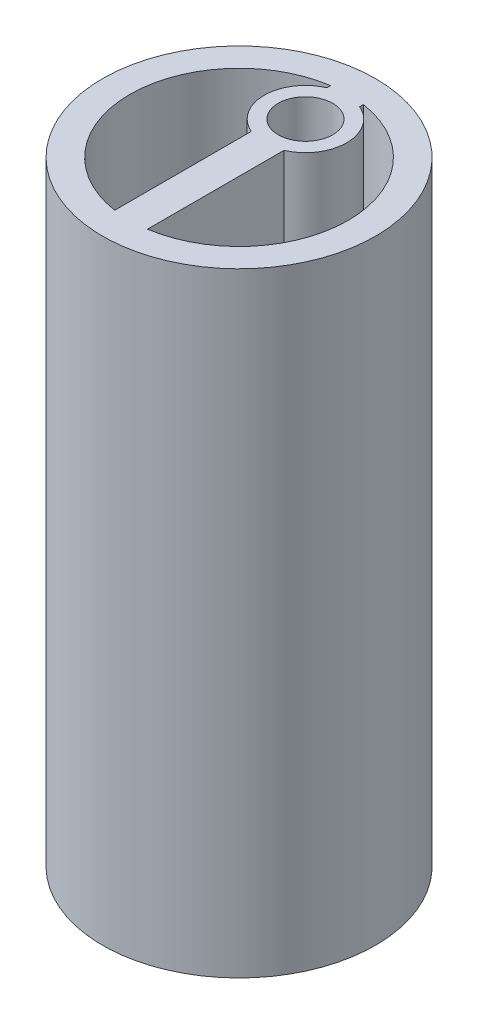
SolidWorks part; units mm, degrees
ref_plane "Front Plane" through (0, 0, 0) normal (0, 0, 1) x (1, 0, 0)
ref_plane "Top Plane" through (0, 0, 0) normal (0, 1, 0) x (1, 0, 0)
ref_plane "Right Plane" through (0, 0, 0) normal (1, 0, 0) x (0, 0, -1)
sketch "Sketch1" plane through (0, 0, 0) normal (0, 1, 0) x (1, 0, 0)
  circle A0 centre (0, 0) radius 10
  circle A1 centre (0, 0) radius 8
  dimension "D1" = 20
  dimension "D2" = 16
extrude "Boss-Extrude1" add sketch "Sketch1" along normal blind 45
sketch "Sketch3" plane through (0, 45, 0) normal (0, 1, 0) x (1, 0, 0)
  line L1 (-1.2, 8.9932) -> (1.2, 8.9932)
  line L2 (-1.2, 8.9932) -> (-1.2, -9.0048)
  line L3 (-1.2, -9.0048) -> (1.2, -9.0048)
  line L4 (1.2, 8.9932) -> (1.2, -9.0048)
  dimension "D1" = 1.2
  dimension "D2" = 1.2
extrude "Boss-Extrude3" add sketch "Sketch3" against normal through all
sketch "Sketch4" plane through (0, 45, 0) normal (0, 1, 0) x (1, 0, 0)
  circle A0 centre (0, 4.8642) radius 3.0196
  point P2 (0, 4.8642)
extrude "Boss-Extrude4" add sketch "Sketch4" against normal through all
sketch "Sketch5" plane through (0, 45, 0) normal (0, 1, 0) x (1, 0, 0)
  circle A0 centre (0, 4.8642) radius 2
  arc A1 (1.2, 2.0932) -> (1.2, 7.6351) centre (0, 4.8642) ccw construction
  dimension "D1" = 4
extrude "Cut-Extrude1" cut sketch "Sketch5" against normal through all
